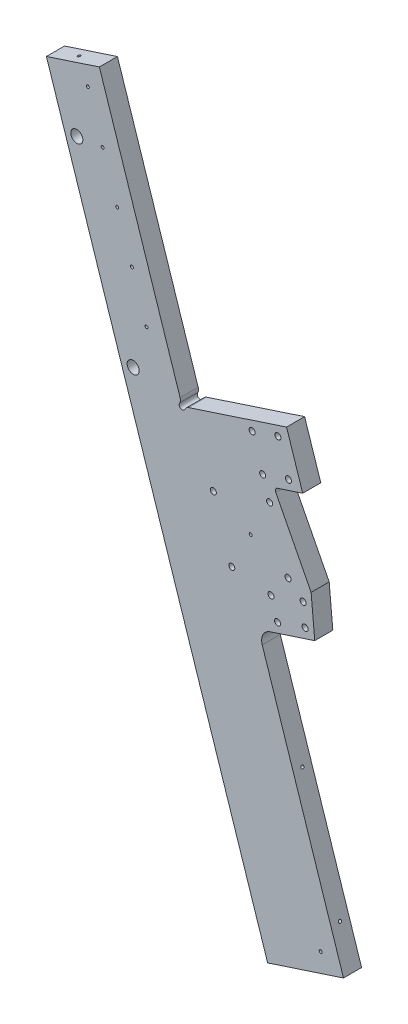
SolidWorks part; units mm, degrees
material "Beech"
ref_plane "Front Plane" through (0, 0, 0) normal (0, 0, 1) x (1, 0, 0)
ref_plane "Top Plane" through (0, 0, 0) normal (0, 1, 0) x (1, 0, 0)
ref_plane "Right Plane" through (0, 0, 0) normal (1, 0, 0) x (0, 0, -1)
sketch "Sketch1" plane through (0, 0, 0) normal (0, 0, 1) x (1, 0, 0)
  line L0 (-247.2747, 82.1423) -> (-327.221, 55.9172)
  line L1 (-439.7405, 215.5744) -> (-258.3751, -337.3104) construction
  line L2 (-258.3751, -337.3104) -> (28.0515, -243.3525) construction
  line L3 (410.7074, -234.518) -> (-159.1322, -247.6741) construction
  line L4 (-327.221, 55.9172) -> (-560.3372, 766.5619)
  line L5 (-560.3372, 766.5619) -> (-614.6401, 748.7487) construction
  line L6 (-271.4742, 155.9135) -> (-270.4845, 152.8966) construction
  line L7 (-313.4082, 283.7475) -> (-139.2341, -247.2147) construction
  line L8 (-327.221, 55.9172) -> (-381.524, 38.1039) construction
  line L14 (-393.1168, 526.7359) -> (-417.2514, 518.8189)
  line L15 (-417.2514, 518.8189) -> (-504.5254, 784.8701)
  line L16 (-504.5254, 784.8701) -> (-560.3372, 766.5619)
  line L17 (-614.6401, 748.7487) -> (-381.524, 38.1039) construction
  line L20 (-247.2747, 82.1423) -> (-393.1168, 526.7359)
  dimension "D2" = 1143
  dimension "D1" = 57.15
  dimension "D3" = 25.4
  dimension "D4" = 280
  dimension "D5" = 395.0968
extrude "Boss-Extrude1" add sketch "Sketch1" against normal blind 19.05
sketch "Sketch2" plane through (0, 0, 0) normal (0, 0, 1) x (1, 0, 0)
  line L0 (-393.1168, 526.7359) -> (-336.9012, 355.365)
  line L1 (-393.1168, 526.7359) -> (-307.3073, 554.8844)
  line L3 (-307.3073, 554.8844) -> (-290.2809, 502.98)
  line L4 (-247.2747, 82.1423) -> (-393.1168, 526.7359) construction
  line L8 (-281.4152, 417.0054) -> (-277.6044, 374.8164)
  line L9 (-277.6044, 374.8164) -> (-336.9012, 355.365)
  line L10 (-281.4152, 417.0054) -> (-349.7663, 394.5838) construction
  line L11 (-290.2809, 502.98) -> (-320.4492, 493.0837)
  line L12 (-320.4492, 493.0837) -> (-281.4152, 417.0054)
  dimension "D2" = 31.75
  dimension "D3" = 84.455
  dimension "D4" = 9
  dimension "D5" = 41.275
  dimension "D6" = 158
extrude "Boss-Extrude2" add sketch "Sketch2" against normal through all
fillet "Fillet1" radius 3.175 1 edges at (-320.4492, 493.0837, -9.525)
fillet "Fillet2" radius 12.7 1 edges at (-336.9012, 355.365, -9.525)
sketch "Sketch47" plane through (0, 0, -19.05) normal (0, 0, -1) x (-1, 0, 0)
  circle A0 centre (417.2514, 518.8189) radius 3.175
  dimension "D1" = 6.35
extrude "Cut-Extrude1" cut sketch "Sketch47" against normal through all both and the other way through all
fillet "Fillet4" radius 6.35 2 edges at (-418.241, 521.8357, -9.525) (-414.2346, 519.8085, -9.525)
hole_wizard " (0.25) Diameter Hole1" positions "Sketch3" profile "Sketch4" hole size "1/4" standard "ANSI Inch" end condition through all
sketch "Sketch3" plane through (0, 0, 0) normal (0, 0, 1) x (1, 0, 0)
  circle A0 centre (-563.4503, 698.5447) radius 2.4575 construction
  point P0 (-563.4503, 698.5447)
  point P6 (-504.0728, 517.5348)
  point P9 (-343.5572, 532.9688)
  point P12 (-316.4058, 541.8754)
  point P15 (-305.3171, 508.072)
  point P18 (-332.4685, 499.1653)
  point P21 (-384.4279, 457.8058)
  point P24 (-325.1579, 477.2484)
  point P27 (-305.7153, 417.9784)
  point P30 (-364.9853, 398.5358)
  point P33 (-323.6987, 393.1105)
  point P36 (-289.8243, 404.2225)
  point P39 (-287.7724, 381.5053)
  point P42 (-316.7714, 371.9927)
sketch "Sketch4" plane through (-563.4503, 698.5447, 0) normal (1, 0, 0) x (0, -1, 0)
  line L0 (0, 0) -> (0, 19.05)
  line L1 (0, 19.05) -> (3.175, 19.05)
  line L2 (3.175, 19.05) -> (3.175, 0)
  line L5 (3.175, 0) -> (0, 0)
  line L11 (0, -6.35) -> (0, 107.95) construction
  dimension "Thru Hole Dia." = 6.35
  dimension "Thru Hole Depth" = 19.05
hole_wizard "1/2 (0.5) Diameter Hole1" positions "Sketch5" profile "Sketch6" hole size "1/2" standard "ANSI Inch"
sketch "Sketch5" plane through (0, 0, 0) normal (0, 0, 1) x (1, 0, 0)
  circle A0 centre (-563.4503, 698.5447) radius 3.175 construction
  circle A1 centre (-504.0728, 517.5348) radius 3.175 construction
  point P0 (-563.4503, 698.5447)
  point P2 (-504.0728, 517.5348)
  point P15 (-316.7714, 371.9927)
  point P18 (-323.6987, 393.1105)
  point P21 (-289.8243, 404.2225)
  point P24 (-287.7724, 381.5053)
  point P27 (-305.7153, 417.9784)
  point P30 (-364.9853, 398.5358)
  point P33 (-384.4279, 457.8058)
  point P36 (-325.1579, 477.2484)
  point P39 (-332.4685, 499.1653)
  point P42 (-305.3171, 508.072)
  point P45 (-316.4058, 541.8754)
  point P48 (-343.5572, 532.9688)
sketch "Sketch6" plane through (-563.4503, 698.5447, 0) normal (1, 0, 0) x (0, -1, 0)
  line L0 (0, 0) -> (0, 19.05)
  line L1 (0, 19.05) -> (6.35, 19.05)
  line L2 (6.35, 19.05) -> (6.35, 0)
  line L5 (6.35, 0) -> (0, 0)
  line L11 (0, -6.35) -> (0, 107.95) construction
  dimension "Thru Hole Dia." = 12.7
  dimension "Thru Hole Depth" = 19.05
hole_wizard "1/4 (0.25) Diameter Hole1" positions "Sketch7" profile "Sketch8" hole size "1/4" standard "ANSI Inch"
sketch "Sketch7" plane through (0, 0, -19.05) normal (0, 0, -1) x (-1, 0, 0)
  circle A0 centre (455.1085, 399.9384) radius 2.4574 construction
  circle A1 centre (514.486, 580.9482) radius 2.4574 construction
  point P0 (514.486, 580.9482)
  point P2 (455.1085, 399.9384)
  point P10 (332.4685, 499.1653)
  point P13 (305.3171, 508.072)
  point P16 (343.5572, 532.9688)
  point P19 (316.4058, 541.8754)
  point P22 (325.1579, 477.2484)
  point P25 (384.4279, 457.8058)
  point P28 (364.9853, 398.5358)
  point P31 (305.7153, 417.9784)
  point P34 (289.8243, 404.2225)
  point P37 (323.6987, 393.1105)
  point P40 (316.7714, 371.9927)
  point P43 (287.7724, 381.5053)
sketch "Sketch8" plane through (-514.486, 580.9482, -19.05) normal (1, 0, 0) x (0, 1, 0)
  line L0 (0, 0) -> (0, 19.05)
  line L1 (0, 19.05) -> (3.175, 19.05)
  line L2 (3.175, 19.05) -> (3.175, 0)
  line L5 (3.175, 0) -> (0, 0)
  line L11 (0, -6.35) -> (0, 107.95) construction
  dimension "Thru Hole Dia." = 6.35
  dimension "Thru Hole Depth" = 19.05
hole_wizard "1/2 (0.5) Diameter Hole2" positions "Sketch9" profile "Sketch10" hole size "1/2" standard "ANSI Inch"
sketch "Sketch9" plane through (0, 0, -19.05) normal (0, 0, -1) x (-1, 0, 0)
  circle A0 centre (455.1085, 399.9384) radius 3.175 construction
  circle A1 centre (514.486, 580.9482) radius 3.175 construction
  point P0 (514.486, 580.9482)
  point P2 (455.1085, 399.9384)
  point P10 (305.3171, 508.072)
  point P13 (316.4058, 541.8754)
  point P16 (343.5572, 532.9688)
  point P19 (332.4685, 499.1653)
  point P22 (325.1579, 477.2484)
  point P25 (384.4279, 457.8058)
  point P28 (364.9853, 398.5358)
  point P31 (305.7153, 417.9784)
  point P34 (323.6987, 393.1105)
  point P37 (289.8243, 404.2225)
  point P40 (287.7724, 381.5053)
  point P43 (316.7714, 371.9927)
sketch "Sketch10" plane through (-514.486, 580.9482, -19.05) normal (1, 0, 0) x (0, 1, 0)
  line L0 (0, 0) -> (0, 19.05)
  line L1 (0, 19.05) -> (6.35, 19.05)
  line L2 (6.35, 19.05) -> (6.35, 0)
  line L5 (6.35, 0) -> (0, 0)
  line L11 (0, -6.35) -> (0, 107.95) construction
  dimension "Thru Hole Dia." = 12.7
  dimension "Thru Hole Depth" = 19.05
hole_wizard "Hole5" positions "Sketch19" profile "Sketch20" legacy
sketch "Sketch19" plane through (313.774, -375.7008, -38.1) normal (0, 0, -1) x (-0.9978, 0.0669, 0)
  line L2 (711.836, 767.6591) -> (859.4878, 708.0039) construction
  point P0 (615.2408, 429.7814)
  point P2 (710.9149, 391.1265)
  point P4 (904.6882, 1078.3844)
  point P6 (976.8119, 1049.2445)
  point P8 (835.9373, 717.5189)
  point P10 (711.836, 767.6591)
sketch "Sketch20" plane through (-271.3134, 94.3056, -38.1) normal (1, 0, 0) x (0, 1, 0)
  line L0 (0, 0) -> (0, 39.0539)
  line L1 (0, 39.0539) -> (1.5875, 38.1)
  line L2 (1.5875, 38.1) -> (1.5875, 4.0177)
  line L3 (1.5875, 4.0177) -> (5.08, 0)
  line L4 (5.08, 0) -> (0, 0)
  line L5 (0, -14.3089) -> (0, 102.4216) construction
  line L6 (0, 39.0539) -> (-1.5875, 38.1) construction
  line L7 (-1.5875, 4.0177) -> (-5.08, 0) construction
  dimension "Diameter" = 3.175
  dimension "Depth" = 38.1
  dimension "C-Sink Diameter" = 10.16
  dimension "C-Sink Angle" = 82
  dimension "Drill Angle" = 118
hole_wizard "Hole6" positions "Sketch21" profile "Sketch22" legacy
sketch "Sketch21" plane through (313.774, -375.7008, -19.05) normal (0, 0, -1) x (-0.9978, 0.0669, 0)
  line L2 (711.836, 767.6591) -> (859.4878, 708.0039) construction
  point P0 (615.2408, 429.7814)
  point P2 (710.9149, 391.1265)
  point P4 (904.6882, 1078.3844)
  point P6 (976.8119, 1049.2445)
  point P8 (835.9373, 717.5189)
  point P10 (711.836, 767.6591)
sketch "Sketch22" plane through (-271.3134, 94.3056, -19.05) normal (1, 0, 0) x (0, 1, 0)
  line L0 (0, 0) -> (0, 39.0539)
  line L1 (0, 39.0539) -> (1.5875, 38.1)
  line L2 (1.5875, 38.1) -> (1.5875, 4.0177)
  line L3 (1.5875, 4.0177) -> (5.08, 0)
  line L4 (5.08, 0) -> (0, 0)
  line L5 (0, -14.3089) -> (0, 102.4216) construction
  line L6 (0, 39.0539) -> (-1.5875, 38.1) construction
  line L7 (-1.5875, 4.0177) -> (-5.08, 0) construction
  dimension "Diameter" = 3.175
  dimension "Depth" = 38.1
  dimension "C-Sink Diameter" = 10.16
  dimension "C-Sink Angle" = 82
  dimension "Drill Angle" = 118
hole_wizard "Hole7" positions "Sketch23" profile "Sketch24" legacy
sketch "Sketch23" plane through (313.774, -375.7008, 19.05) normal (0, 0, 1) x (0.9978, -0.0669, 0)
  point P1 (-710.9149, 391.1265)
  point P3 (-615.2408, 429.7814)
  point P5 (-711.836, 767.6591)
  point P7 (-835.9373, 717.5189)
  point P9 (-904.6882, 1078.3844)
  point P11 (-976.8119, 1049.2445)
sketch "Sketch24" plane through (-369.3607, 62.1426, 19.05) normal (1, 0, 0) x (0, -1, 0)
  line L0 (0, 0) -> (0, 39.0539)
  line L1 (0, 39.0539) -> (1.5875, 38.1)
  line L2 (1.5875, 38.1) -> (1.5875, 4.0177)
  line L3 (1.5875, 4.0177) -> (5.08, 0)
  line L4 (5.08, 0) -> (0, 0)
  line L5 (0, -14.3089) -> (0, 102.4216) construction
  line L6 (0, 39.0539) -> (-1.5875, 38.1) construction
  line L7 (-1.5875, 4.0177) -> (-5.08, 0) construction
  dimension "Diameter" = 3.175
  dimension "Depth" = 38.1
  dimension "C-Sink Diameter" = 10.16
  dimension "C-Sink Angle" = 82
  dimension "Drill Angle" = 118
hole_wizard "Hole8" positions "Sketch25" profile "Sketch26" legacy
sketch "Sketch25" plane through (313.774, -375.7008, 0) normal (0, 0, 1) x (0.9978, -0.0669, 0)
  point P1 (-710.9149, 391.1265)
  point P3 (-615.2408, 429.7814)
  point P5 (-711.836, 767.6591)
  point P7 (-835.9373, 717.5189)
  point P9 (-904.6882, 1078.3844)
  point P11 (-976.8119, 1049.2445)
sketch "Sketch26" plane through (-369.3607, 62.1426, 0) normal (1, 0, 0) x (0, -1, 0)
  line L0 (0, 0) -> (0, 39.0539)
  line L1 (0, 39.0539) -> (1.5875, 38.1)
  line L2 (1.5875, 38.1) -> (1.5875, 4.0177)
  line L3 (1.5875, 4.0177) -> (5.08, 0)
  line L4 (5.08, 0) -> (0, 0)
  line L5 (0, -14.3089) -> (0, 102.4216) construction
  line L6 (0, 39.0539) -> (-1.5875, 38.1) construction
  line L7 (-1.5875, 4.0177) -> (-5.08, 0) construction
  dimension "Diameter" = 3.175
  dimension "Depth" = 38.1
  dimension "C-Sink Diameter" = 10.16
  dimension "C-Sink Angle" = 82
  dimension "Drill Angle" = 118
hole_wizard "Hole9" positions "Sketch27" profile "Sketch28" legacy
sketch "Sketch27" plane through (313.774, -375.7008, -38.1) normal (0, 0, -1) x (-0.9978, 0.0669, 0)
  line L0 (904.6882, 1078.3844) -> (811.6921, 848.211) construction
  line L4 (858.1902, 963.2977) -> (876.6817, 1009.0658)
  line L5 (876.6817, 1009.0658) -> (895.1732, 1054.8339)
  line L7 (858.1902, 963.2977) -> (875.853, 956.1614) construction
  point P20 (885.9274, 1031.9499)
  point P22 (867.4359, 986.1818)
  point P25 (830.4529, 894.6455)
  point P26 (848.9444, 940.4136)
sketch "Sketch28" plane through (-470.3068, 619.4382, -38.1) normal (1, 0, 0) x (0, 1, 0)
  line L0 (0, 0) -> (0, 58.1039)
  line L1 (0, 58.1039) -> (1.5875, 57.15)
  line L2 (1.5875, 57.15) -> (1.5875, 4.0177)
  line L3 (1.5875, 4.0177) -> (5.08, 0)
  line L4 (5.08, 0) -> (0, 0)
  line L5 (0, -14.3089) -> (0, 102.4216) construction
  line L6 (0, 58.1039) -> (-1.5875, 57.15) construction
  line L7 (-1.5875, 4.0177) -> (-5.08, 0) construction
  dimension "Diameter" = 3.175
  dimension "Depth" = 57.15
  dimension "C-Sink Diameter" = 10.16
  dimension "C-Sink Angle" = 82
  dimension "Drill Angle" = 118
hole_wizard "Hole10" positions "Sketch29" profile "Sketch30" legacy
sketch "Sketch29" plane through (313.774, -375.7008, -57.15) normal (0, 0, -1) x (-0.9978, 0.0669, 0)
  line L0 (904.6882, 1078.3844) -> (811.6921, 848.211) construction
  line L4 (858.1902, 963.2977) -> (876.6817, 1009.0658)
  line L5 (876.6817, 1009.0658) -> (895.1732, 1054.8339)
  line L7 (858.1902, 963.2977) -> (875.853, 956.1614) construction
  point P20 (885.9274, 1031.9499)
  point P22 (867.4359, 986.1818)
  point P25 (830.4529, 894.6455)
  point P26 (848.9444, 940.4136)
sketch "Sketch30" plane through (-470.3068, 619.4382, -57.15) normal (1, 0, 0) x (0, 1, 0)
  line L0 (0, 0) -> (0, 58.1039)
  line L1 (0, 58.1039) -> (1.5875, 57.15)
  line L2 (1.5875, 57.15) -> (1.5875, 4.0177)
  line L3 (1.5875, 4.0177) -> (5.08, 0)
  line L4 (5.08, 0) -> (0, 0)
  line L5 (0, -14.3089) -> (0, 102.4216) construction
  line L6 (0, 58.1039) -> (-1.5875, 57.15) construction
  line L7 (-1.5875, 4.0177) -> (-5.08, 0) construction
  dimension "Diameter" = 3.175
  dimension "Depth" = 57.15
  dimension "C-Sink Diameter" = 10.16
  dimension "C-Sink Angle" = 82
  dimension "Drill Angle" = 118
hole_wizard "Hole11" positions "Sketch31" profile "Sketch32" legacy
sketch "Sketch31" plane through (-45.1028, -493.4248, -72.025) normal (0.9502, 0.3117, 0) x (0, 0, -1)
  point P49 (175, 685.961)
  point P51 (175, 549.8373)
  point P53 (175, 413.7135)
  point P67 (81.55, 779.6497)
  point P73 (81.55, 652.3446)
  point P79 (62.5, 662.9534)
  point P83 (62.5, 769.041)
  point P103 (-62.5, 769.041)
  point P105 (-62.5, 662.9534)
  point P106 (-81.55, 652.3446)
  point P109 (-81.55, 779.6497)
  point P110 (-175, 413.7135)
  point P111 (-175, 549.8373)
  point P112 (-175, 685.961)
  point P115 (-82.7375, 600.3846)
  point P117 (0, 600.3846)
  point P119 (82.7375, 600.3846)
  point P129 (0, 376.7378)
  point P131 (-82.7375, 376.7378)
  point P133 (82.7375, 376.7378)
sketch "Sketch32" plane through (-258.912, 158.3636, -247.025) normal (0, 0, 1) x (-0.3117, 0.9502, 0)
  line L0 (0, 0) -> (0, 32.7039)
  line L1 (0, 32.7039) -> (1.5875, 31.75)
  line L2 (1.5875, 31.75) -> (1.5875, 4.0177)
  line L3 (1.5875, 4.0177) -> (5.08, 0)
  line L4 (5.08, 0) -> (0, 0)
  line L5 (0, -14.3089) -> (0, 102.4216) construction
  line L6 (0, 32.7039) -> (-1.5875, 31.75) construction
  line L7 (-1.5875, 4.0177) -> (-5.08, 0) construction
  dimension "Diameter" = 3.175
  dimension "Depth" = 31.75
  dimension "C-Sink Diameter" = 10.16
  dimension "C-Sink Angle" = 82
  dimension "Drill Angle" = 118
hole_wizard "Hole12" positions "Sketch33" profile "Sketch34" legacy
sketch "Sketch33" plane through (-45.1028, -493.4248, -91.075) normal (0.9502, 0.3117, 0) x (0, 0, -1)
  point P49 (175, 685.961)
  point P51 (175, 549.8373)
  point P53 (175, 413.7135)
  point P67 (81.55, 779.6497)
  point P73 (81.55, 652.3446)
  point P79 (62.5, 662.9534)
  point P83 (62.5, 769.041)
  point P103 (-62.5, 769.041)
  point P105 (-62.5, 662.9534)
  point P106 (-81.55, 652.3446)
  point P109 (-81.55, 779.6497)
  point P110 (-175, 413.7135)
  point P111 (-175, 549.8373)
  point P112 (-175, 685.961)
  point P115 (-82.7375, 600.3846)
  point P117 (0, 600.3846)
  point P119 (82.7375, 600.3846)
  point P129 (0, 376.7378)
  point P131 (-82.7375, 376.7378)
  point P133 (82.7375, 376.7378)
sketch "Sketch34" plane through (-258.912, 158.3636, -266.075) normal (0, 0, 1) x (-0.3117, 0.9502, 0)
  line L0 (0, 0) -> (0, 32.7039)
  line L1 (0, 32.7039) -> (1.5875, 31.75)
  line L2 (1.5875, 31.75) -> (1.5875, 4.0177)
  line L3 (1.5875, 4.0177) -> (5.08, 0)
  line L4 (5.08, 0) -> (0, 0)
  line L5 (0, -14.3089) -> (0, 102.4216) construction
  line L6 (0, 32.7039) -> (-1.5875, 31.75) construction
  line L7 (-1.5875, 4.0177) -> (-5.08, 0) construction
  dimension "Diameter" = 3.175
  dimension "Depth" = 31.75
  dimension "C-Sink Diameter" = 10.16
  dimension "C-Sink Angle" = 82
  dimension "Drill Angle" = 118
hole_wizard "Hole13" positions "Sketch35" profile "Sketch36" legacy
sketch "Sketch35" plane through (-45.1028, -493.4248, 52.975) normal (0.9502, 0.3117, 0) x (0, 0, -1)
  point P49 (175, 685.961)
  point P51 (175, 549.8373)
  point P53 (175, 413.7135)
  point P67 (81.55, 779.6497)
  point P73 (81.55, 652.3446)
  point P79 (62.5, 662.9534)
  point P83 (62.5, 769.041)
  point P103 (-62.5, 769.041)
  point P105 (-62.5, 662.9534)
  point P106 (-81.55, 652.3446)
  point P109 (-81.55, 779.6497)
  point P110 (-175, 413.7135)
  point P111 (-175, 549.8373)
  point P112 (-175, 685.961)
  point P115 (-82.7375, 600.3846)
  point P117 (0, 600.3846)
  point P119 (82.7375, 600.3846)
  point P129 (0, 376.7378)
  point P131 (-82.7375, 376.7378)
  point P133 (82.7375, 376.7378)
sketch "Sketch36" plane through (-258.912, 158.3636, -122.025) normal (0, 0, 1) x (-0.3117, 0.9502, 0)
  line L0 (0, 0) -> (0, 32.7039)
  line L1 (0, 32.7039) -> (1.5875, 31.75)
  line L2 (1.5875, 31.75) -> (1.5875, 4.0177)
  line L3 (1.5875, 4.0177) -> (5.08, 0)
  line L4 (5.08, 0) -> (0, 0)
  line L5 (0, -14.3089) -> (0, 102.4216) construction
  line L6 (0, 32.7039) -> (-1.5875, 31.75) construction
  line L7 (-1.5875, 4.0177) -> (-5.08, 0) construction
  dimension "Diameter" = 3.175
  dimension "Depth" = 31.75
  dimension "C-Sink Diameter" = 10.16
  dimension "C-Sink Angle" = 82
  dimension "Drill Angle" = 118
hole_wizard "Hole14" positions "Sketch37" profile "Sketch38" legacy
sketch "Sketch37" plane through (-45.1028, -493.4248, 72.025) normal (0.9502, 0.3117, 0) x (0, 0, -1)
  point P49 (175, 685.961)
  point P51 (175, 549.8373)
  point P53 (175, 413.7135)
  point P67 (81.55, 779.6497)
  point P73 (81.55, 652.3446)
  point P79 (62.5, 662.9534)
  point P83 (62.5, 769.041)
  point P103 (-62.5, 769.041)
  point P105 (-62.5, 662.9534)
  point P106 (-81.55, 652.3446)
  point P109 (-81.55, 779.6497)
  point P110 (-175, 413.7135)
  point P111 (-175, 549.8373)
  point P112 (-175, 685.961)
  point P115 (-82.7375, 600.3846)
  point P117 (0, 600.3846)
  point P119 (82.7375, 600.3846)
  point P129 (0, 376.7378)
  point P131 (-82.7375, 376.7378)
  point P133 (82.7375, 376.7378)
sketch "Sketch38" plane through (-258.912, 158.3636, -102.975) normal (0, 0, 1) x (-0.3117, 0.9502, 0)
  line L0 (0, 0) -> (0, 32.7039)
  line L1 (0, 32.7039) -> (1.5875, 31.75)
  line L2 (1.5875, 31.75) -> (1.5875, 4.0177)
  line L3 (1.5875, 4.0177) -> (5.08, 0)
  line L4 (5.08, 0) -> (0, 0)
  line L5 (0, -14.3089) -> (0, 102.4216) construction
  line L6 (0, 32.7039) -> (-1.5875, 31.75) construction
  line L7 (-1.5875, 4.0177) -> (-5.08, 0) construction
  dimension "Diameter" = 3.175
  dimension "Depth" = 31.75
  dimension "C-Sink Diameter" = 10.16
  dimension "C-Sink Angle" = 82
  dimension "Drill Angle" = 118
hole_wizard "Hole15" positions "Sketch39" profile "Sketch40" legacy
sketch "Sketch39" plane through (-155.2175, -529.5463, 72.025) normal (-0.9502, -0.3117, 0) x (0, 0, 1)
  point P0 (-78.375, 1310.1878)
  point P3 (-78.375, 1138.7378)
  point P6 (78.375, 1138.7378)
  point P9 (78.375, 1310.1878)
sketch "Sketch40" plane through (-563.5938, 715.3717, -6.35) normal (0, 0, 1) x (0.3117, -0.9502, 0)
  line L0 (0, 0) -> (0, 32.7039)
  line L1 (0, 32.7039) -> (1.5875, 31.75)
  line L2 (1.5875, 31.75) -> (1.5875, 4.0177)
  line L3 (1.5875, 4.0177) -> (5.08, 0)
  line L4 (5.08, 0) -> (0, 0)
  line L5 (0, -14.3089) -> (0, 102.4216) construction
  line L6 (0, 32.7039) -> (-1.5875, 31.75) construction
  line L7 (-1.5875, 4.0177) -> (-5.08, 0) construction
  dimension "Diameter" = 3.175
  dimension "Depth" = 31.75
  dimension "C-Sink Diameter" = 10.16
  dimension "C-Sink Angle" = 82
  dimension "Drill Angle" = 118
hole_wizard "Hole16" positions "Sketch41" profile "Sketch42" legacy
sketch "Sketch41" plane through (-155.2175, -529.5463, -91.075) normal (-0.9502, -0.3117, 0) x (0, 0, 1)
  point P0 (-78.375, 1310.1878)
  point P3 (-78.375, 1138.7378)
  point P6 (78.375, 1138.7378)
  point P9 (78.375, 1310.1878)
sketch "Sketch42" plane through (-617.8967, 697.5585, -169.45) normal (0, 0, 1) x (0.3117, -0.9502, 0)
  line L0 (0, 0) -> (0, 32.7039)
  line L1 (0, 32.7039) -> (1.5875, 31.75)
  line L2 (1.5875, 31.75) -> (1.5875, 4.0177)
  line L3 (1.5875, 4.0177) -> (5.08, 0)
  line L4 (5.08, 0) -> (0, 0)
  line L5 (0, -14.3089) -> (0, 102.4216) construction
  line L6 (0, 32.7039) -> (-1.5875, 31.75) construction
  line L7 (-1.5875, 4.0177) -> (-5.08, 0) construction
  dimension "Diameter" = 3.175
  dimension "Depth" = 31.75
  dimension "C-Sink Diameter" = 10.16
  dimension "C-Sink Angle" = 82
  dimension "Drill Angle" = 118
hole_wizard "Hole17" positions "Sketch43" profile "Sketch44" legacy
sketch "Sketch43" plane through (-111.4259, 920.5033, 72.025) normal (-0.3117, 0.9502, 0) x (0, 0, -1)
  line L0 (91.075, 448.3363) -> (-91.075, 448.3363) construction
  point P0 (81.55, 448.3363)
  point P2 (-81.55, 448.3363)
sketch "Sketch44" plane through (-537.4274, 780.7601, -9.525) normal (0, 0, 1) x (-0.9502, -0.3117, 0)
  line L0 (0, 0) -> (0, 32.7039)
  line L1 (0, 32.7039) -> (1.5875, 31.75)
  line L2 (1.5875, 31.75) -> (1.5875, 4.0177)
  line L3 (1.5875, 4.0177) -> (5.08, 0)
  line L4 (5.08, 0) -> (0, 0)
  line L5 (0, -14.3089) -> (0, 102.4216) construction
  line L6 (0, 32.7039) -> (-1.5875, 31.75) construction
  line L7 (-1.5875, 4.0177) -> (-5.08, 0) construction
  dimension "Diameter" = 3.175
  dimension "Depth" = 31.75
  dimension "C-Sink Diameter" = 10.16
  dimension "C-Sink Angle" = 82
  dimension "Drill Angle" = 118
hole_wizard "Hole18" positions "Sketch45" profile "Sketch46" legacy
sketch "Sketch45" plane through (-111.4259, 920.5033, -91.075) normal (-0.3117, 0.9502, 0) x (0, 0, -1)
  line L0 (91.075, 476.9113) -> (-91.075, 476.9113) construction
  point P0 (81.55, 476.9113)
  point P2 (-81.55, 476.9113)
sketch "Sketch46" plane through (-564.5789, 771.8534, -172.625) normal (0, 0, 1) x (-0.9502, -0.3117, 0)
  line L0 (0, 0) -> (0, 32.7039)
  line L1 (0, 32.7039) -> (1.5875, 31.75)
  line L2 (1.5875, 31.75) -> (1.5875, 4.0177)
  line L3 (1.5875, 4.0177) -> (5.08, 0)
  line L4 (5.08, 0) -> (0, 0)
  line L5 (0, -14.3089) -> (0, 102.4216) construction
  line L6 (0, 32.7039) -> (-1.5875, 31.75) construction
  line L7 (-1.5875, 4.0177) -> (-5.08, 0) construction
  dimension "Diameter" = 3.175
  dimension "Depth" = 31.75
  dimension "C-Sink Diameter" = 10.16
  dimension "C-Sink Angle" = 82
  dimension "Drill Angle" = 118
hole_wizard "1/2 (0.5) Diameter Hole3" positions "Sketch48" profile "Sketch49" hole size "1/2" standard "ANSI Inch" end condition up to next
sketch "Sketch48" plane through (0, 0, 0) normal (0, 0, 1) x (1, 0, 0)
  line L0 (-560.3372, 766.5619) -> (-327.221, 55.9172) construction
  line L1 (-528.2903, 709.6137) -> (-468.9128, 528.6039) construction
  point P0 (-468.9128, 528.6039)
  point P2 (-528.2903, 709.6137)
  dimension "D1" = 190.5
  dimension "D2" = 12.7
sketch "Sketch49" plane through (-468.9128, 528.6039, 0) normal (1, 0, 0) x (0, -1, 0)
  line L0 (0, 0) -> (0, 19.05)
  line L1 (0, 19.05) -> (6.35, 19.05)
  line L2 (6.35, 19.05) -> (6.35, 0)
  line L5 (6.35, 0) -> (0, 0)
  line L11 (0, -6.35) -> (0, 107.95) construction
  dimension "Thru Hole Dia." = 12.7
  dimension "Thru Hole Depth" = 19.05
